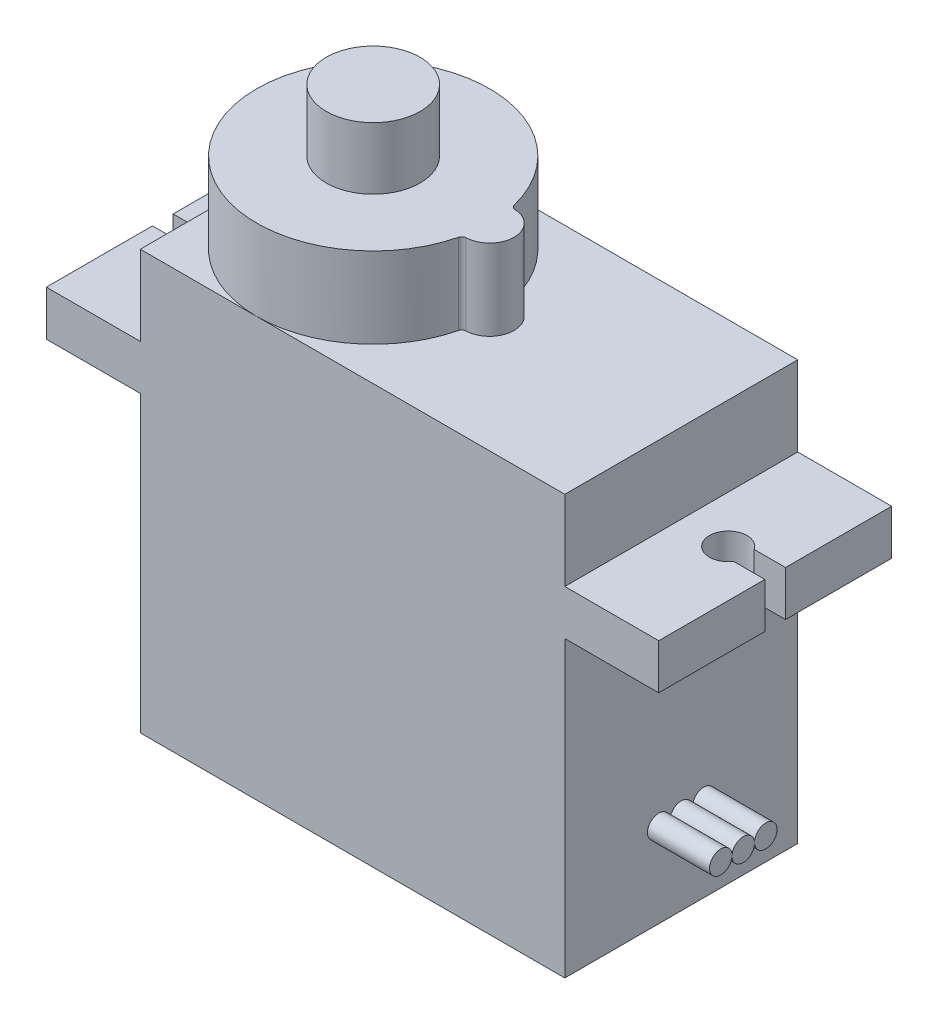
SolidWorks part; units mm, degrees
ref_plane "Front Plane" through (0, 0, 0) normal (0, 0, 1) x (1, 0, 0)
ref_plane "Top Plane" through (0, 0, 0) normal (0, 1, 0) x (1, 0, 0)
ref_plane "Right Plane" through (0, 0, 0) normal (1, 0, 0) x (0, 0, -1)
sketch "Sketch1" plane through (0, 0, 0) normal (0, 1, 0) x (1, 0, 0)
  line L1 (-11.3, -6.2) -> (11.3, -6.2)
  line L2 (-11.3, -6.2) -> (-11.3, 6.2)
  line L3 (-11.3, 6.2) -> (11.3, 6.2)
  line L4 (11.3, -6.2) -> (11.3, 6.2)
  line L5 (-11.3, -6.2) -> (11.3, 6.2) construction
  line L6 (-11.3, 6.2) -> (11.3, -6.2) construction
  point P0 (0, 0)
  dimension "D1" = 22.6
  dimension "D2" = 12.4
extrude "Boss-Extrude1" add sketch "Sketch1" along normal blind 22.3
sketch "Sketch2" plane through (0, 0, 6.2) normal (0, 0, 1) x (1, 0, 0)
  line L0 (11.3, 22.3) -> (11.3, 0) construction
  line L1 (11.3, 18.05) -> (16.3, 18.05)
  line L2 (11.3, 18.05) -> (11.3, 15.65)
  line L3 (11.3, 15.65) -> (16.3, 15.65)
  line L4 (16.3, 18.05) -> (16.3, 15.65)
  line L5 (-11.3, 22.3) -> (11.3, 22.3) construction
  line L6 (0, 0) -> (0, 16.9821) construction
  line L7 (-16.3, 18.05) -> (-16.3, 15.65)
  line L8 (-11.3, 15.65) -> (-16.3, 15.65)
  line L9 (-11.3, 18.05) -> (-11.3, 15.65)
  line L10 (-11.3, 18.05) -> (-16.3, 18.05)
  dimension "D1" = 4.25
  dimension "D2" = 2.4
  dimension "D3" = 5
extrude "Boss-Extrude2" add sketch "Sketch2" against normal up to surface (12.4 mm away) up to face at (0, 11.15, -6.2)
sketch "Sketch3" plane through (0, 18.05, 0) normal (0, 1, 0) x (1, 0, 0)
  line L0 (0, 0) -> (0, 7.2762) construction
  line L1 (13.8, 0) -> (0, 0) construction
  line L2 (14.6352, 0.55) -> (16.3, 0.55)
  line L3 (16.3, 6.2) -> (16.3, -6.2) construction
  line L4 (16.3, 0.55) -> (16.3, -0.55)
  line L5 (16.3, -0.55) -> (14.6352, -0.55)
  line L6 (-16.3, -0.55) -> (-14.6352, -0.55)
  line L7 (-16.3, 0.55) -> (-16.3, -0.55)
  line L8 (-14.6352, 0.55) -> (-16.3, 0.55)
  arc A0 (14.6352, 0.55) -> (14.6352, -0.55) centre (13.8, 0) ccw
  arc A1 (-14.6352, 0.55) -> (-14.6352, -0.55) centre (-13.8, 0) cw
  dimension "D3" = 2
  dimension "D1" = 2.5
  dimension "D2" = 1.1
extrude "Cut-Extrude1" cut sketch "Sketch3" against normal through all
sketch "Sketch4" plane through (0, 22.3, 0) normal (0, 1, 0) x (1, 0, 0)
  line L0 (-11.3, 6.2) -> (-11.3, -6.2) construction
  line L1 (11.3, 6.2) -> (-11.3, 6.2) construction
  arc A0 (0.9186, 1.4888) -> (0.9186, -1.4888) centre (-5.1, 0) ccw
  arc A1 (1.1514, -1.299) -> (1.1514, 1.299) centre (1.1, 0) ccw
  arc A2 (1.1514, -1.299) -> (0.9186, -1.4888) centre (1.1613, -1.5488) ccw
  arc A3 (1.1514, 1.299) -> (0.9186, 1.4888) centre (1.1613, 1.5488) cw
  dimension "D1" = 12.4
  dimension "D2" = 2.6
  dimension "D3" = 0.25
extrude "Boss-Extrude3" add sketch "Sketch4" along normal blind 4.3
sketch "Sketch5" plane through (0, 26.6, 0) normal (0, 1, 0) x (1, 0, 0)
  circle A0 centre (-5.1, 0) radius 2.5
  dimension "D1" = 5
extrude "Boss-Extrude4" add sketch "Sketch5" along normal blind 3.3
sketch "Sketch6" plane through (11.3, 0, 0) normal (1, 0, 0) x (0, 0, -1)
  line L0 (0, 4.4688) -> (0, 0) construction
  line L1 (-6.2, 0) -> (6.2, 0) construction
  line L2 (-1.1996, 4.5) -> (1.1996, 4.5) construction
  line L4 (6.2, 15.65) -> (6.2, 0) construction
  circle A0 centre (0, 4.4688) radius 0.6
  circle A1 centre (1.1996, 4.5) radius 0.6
  circle A2 centre (-1.1996, 4.5) radius 0.6
  dimension "D1" = 1.2
  dimension "D2" = 4.5
  dimension "D3" = 5.0004
extrude "Boss-Extrude7" add sketch "Sketch6" along normal blind 3.3 separate body contours A1 | A0 | A2
